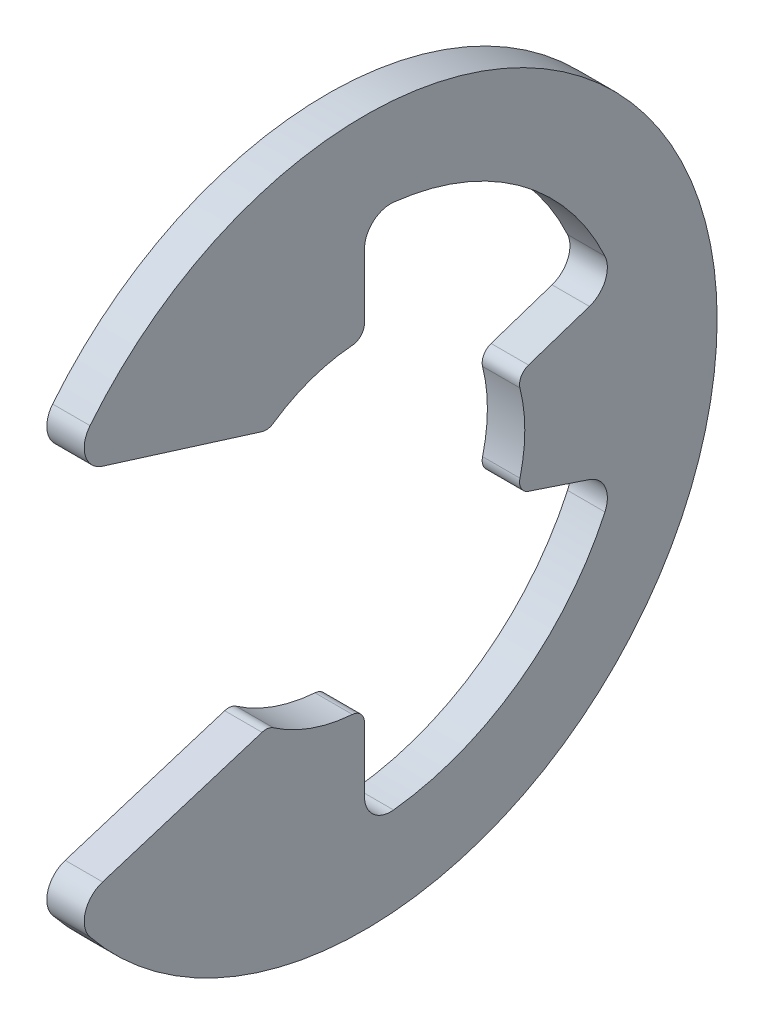
SolidWorks part; units mm, degrees
ref_plane "Front" through (0, 0, 0) normal (0, 0, 1) x (1, 0, 0)
ref_plane "Top" through (0, 0, 0) normal (0, 1, 0) x (1, 0, 0)
ref_plane "Right" through (0, 0, 0) normal (1, 0, 0) x (0, 0, -1)
sketch "Sketch1" plane through (0, 0, 0) normal (1, 0, 0) x (0, 0, -1)
  line L0 (-7.0487, -4.5358) -> (-2.286, -3.048)
  line L1 (-7.0487, 4.5358) -> (-2.286, 3.048)
  line L2 (0, -3.81) -> (0, -6.2926)
  line L3 (0, 3.81) -> (0, 6.2926)
  line L4 (3.6145, -1.2048) -> (5.9697, -1.9899)
  line L5 (3.6145, 1.2048) -> (5.9697, 1.9899)
  line L6 (0, 0) -> (-3.81, 0) construction
  line L7 (3.6145, 1.2048) -> (3.6145, -1.2048) construction
  line L8 (0, -3.81) -> (-2.286, -3.048) construction
  line L9 (0, 8.382) -> (0, -8.382) construction
  circle A2 centre (0, 0) radius 3.81 construction
  arc A3 (-7.0487, -4.5358) -> (-7.0487, 4.5358) centre (0, 0) ccw
  arc A4 (-2.286, -3.048) -> (0, -3.81) centre (0, 0) ccw
  arc A5 (-2.286, 3.048) -> (0, 3.81) centre (0, 0) cw
  arc A6 (3.6145, 1.2048) -> (3.6145, -1.2048) centre (0, 0) cw
  arc A7 (0, -6.2926) -> (5.9697, -1.9899) centre (0, 0) ccw
  arc A8 (5.9697, 1.9899) -> (0, 6.2926) centre (0, 0) ccw
  point P8 (0, 3.81)
  point P12 (0, 8.382)
  dimension "Free Diameter" = 7.62
  dimension "D1" = 6.2926
  dimension "Ring OD" = 16.764
  dimension "D2" = 4.4555
  dimension "D10" = 6.096
sketch "Sketch4" plane through (0, 0, 0) normal (0, 0, 1) x (1, 0, 0)
  line L0 (-0.4445, 8.382) -> (0.4445, 8.382) construction
  point P3 (0, 8.382)
  dimension "Ring Thickness" = 0.889
sketch "Sketch3" plane through (0, 0, 0) normal (1, 0, 0) x (0, 0, -1)
  line L6 (3.6145, -1.2048) -> (5.9697, -1.9899)
  line L7 (0, -6.2926) -> (0, -3.81)
  line L8 (-2.286, -3.048) -> (-7.0487, -4.5358)
  line L9 (-7.0487, 4.5358) -> (-2.286, 3.048)
  line L10 (0, 3.81) -> (0, 6.2926)
  line L11 (5.9697, 1.9899) -> (3.6145, 1.2048)
  line L12 (3.6145, -1.2048) -> (5.9697, -1.9899)
  line L13 (0, -6.2926) -> (0, -3.81)
  line L14 (-2.286, -3.048) -> (-7.0487, -4.5358)
  line L15 (-7.0487, 4.5358) -> (-2.286, 3.048)
  line L16 (0, 3.81) -> (0, 6.2926)
  line L17 (5.9697, 1.9899) -> (3.6145, 1.2048)
  arc A6 (0, -6.2926) -> (5.9697, -1.9899) centre (0, 0) ccw
  arc A7 (-2.286, -3.048) -> (0, -3.81) centre (0, 0) ccw
  arc A8 (-7.0487, -4.5358) -> (-7.0487, 4.5358) centre (0, 0) ccw
  arc A9 (0, 3.81) -> (-2.286, 3.048) centre (0, 0) ccw
  arc A10 (5.9697, 1.9899) -> (0, 6.2926) centre (0, 0) ccw
  arc A11 (3.6145, -1.2048) -> (3.6145, 1.2048) centre (0, 0) ccw
  arc A12 (0, -6.2926) -> (5.9697, -1.9899) centre (0, 0) ccw
  arc A13 (-2.286, -3.048) -> (0, -3.81) centre (0, 0) ccw
  arc A14 (-7.0487, -4.5358) -> (-7.0487, 4.5358) centre (0, 0) ccw
  arc A15 (0, 3.81) -> (-2.286, 3.048) centre (0, 0) ccw
  arc A16 (5.9697, 1.9899) -> (0, 6.2926) centre (0, 0) ccw
  arc A17 (3.6145, -1.2048) -> (3.6145, 1.2048) centre (0, 0) ccw
  dimension "D1" = 0
extrude "Boss-Extrude1" add sketch "Sketch3" along normal up to vertex (0.4445 mm away) and the other way up to vertex (0.4445 mm away) up to point (0.4445, 8.382, 0) other way up to point (-0.4445, 8.382, 0)
fillet "Fillet1" radius 0.6223 6 edges at (0, -6.2926, 0) (0, -1.9899, -5.9697) (0, 1.9899, -5.9697) (0, 6.2926, 0) (0, -4.5358, 7.0487) (0, 4.5358, 7.0487)
fillet "Fillet2" radius 0.3111 6 edges at (0, -3.81, 0) (0, -3.048, 2.286) (0, 1.2048, -3.6145) (0, -1.2048, -3.6145) (0, 3.048, 2.286) (0, 3.81, 0)
equation "\"D1@Sketch1\" =  ( \"Ring OD@Sketch1\" + \"Free Diameter@Sketch1\" )  / 3.875"
equation "\"D10@Sketch1\"=\"Free Diameter@Sketch1\" * .8"
equation "\"D1@Fillet1\"=\"Ring Thickness@Sketch4\"*.7"
equation "\"D1@Fillet2\"=\"D1@Fillet1\"/2"
